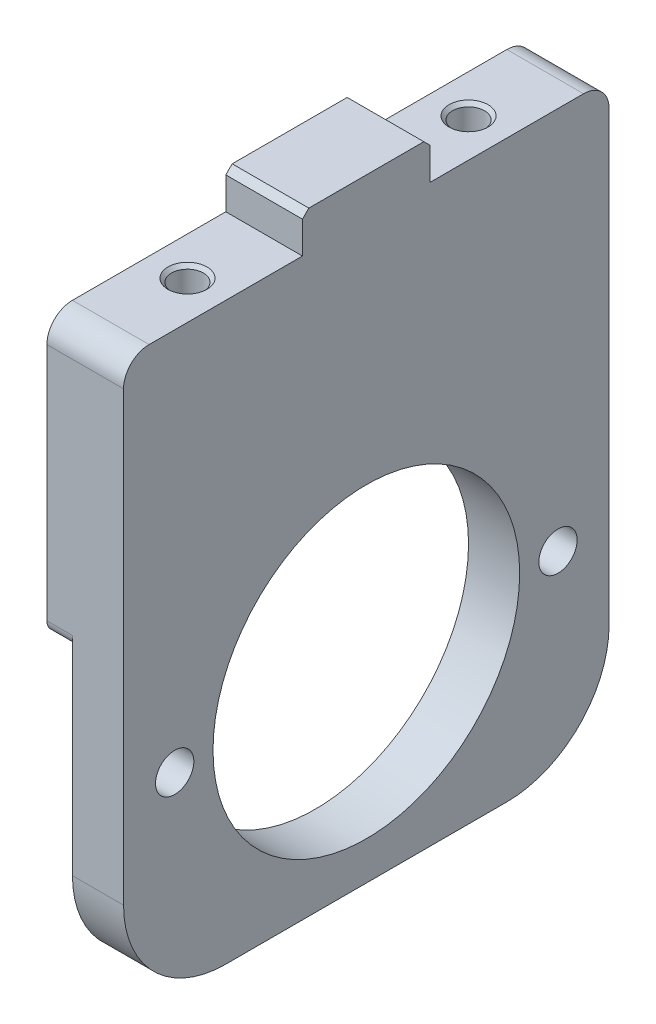
SolidWorks part; units mm, degrees
material "6061 合金"
ref_plane "前视基准面" through (0, 0, 0) normal (0, 0, 1) x (1, 0, 0)
ref_plane "上视基准面" through (0, 0, 0) normal (0, 1, 0) x (1, 0, 0)
ref_plane "右视基准面" through (0, 0, 0) normal (1, 0, 0) x (0, 0, -1)
sketch "草图1" plane through (0, 0, 0) normal (1, 0, 0) x (0, 0, -1)
  line L1 (-19, 22.5) -> (19, 22.5)
  line L2 (-19, 22.5) -> (-19, -22.5)
  line L3 (-19, -22.5) -> (19, -22.5)
  line L4 (19, 22.5) -> (19, -22.5)
  line L5 (-19, 22.5) -> (19, -22.5) construction
  line L6 (-19, -22.5) -> (19, 22.5) construction
  point P0 (0, 0)
  dimension "D1" = 45
  dimension "D2" = 38
extrude "凸台-拉伸1" add sketch "草图1" along normal blind 6
sketch "草图2" plane through (0, 0, 0) normal (-1, 0, 0) x (0, 0, 1)
  line L0 (0, 21.1574) -> (0, -25.7168) construction
  line L1 (0, -7.5) -> (15, -7.5) construction
  line L2 (19, -22.5) -> (-19, -22.5) construction
  circle A0 centre (0, -7.5) radius 12
  circle A1 centre (15, -7.5) radius 1.5
  circle A2 centre (-15, -7.5) radius 1.5
  dimension "D1" = 24
  dimension "D2" = 3
  dimension "D3" = 30
  dimension "D4" = 15
extrude "切除-拉伸1" cut sketch "草图2" against normal through all
sketch "草图3" plane through (0, 0, 0) normal (-1, 0, 0) x (0, 0, 1)
  line L0 (19.25, -7.5) -> (19.25, -22.5)
  line L1 (19, -22.5) -> (-19, -22.5) construction
  line L2 (-19.25, -7.5) -> (-19.25, -22.5)
  line L3 (-19.25, -22.5) -> (19.25, -22.5)
  arc A0 (19.25, -7.5) -> (-19.25, -7.5) centre (0, -7.5) ccw
  dimension "D1" = 38.5
extrude "切除-拉伸2" cut sketch "草图3" against normal blind 2
fillet "圆角2" radius 1 2 edges at (1, -4.4077, -19) (1, -4.4077, 19)
fillet "圆角3" radius 8 2 edges at (4, -22.5, -19) (4, -22.5, 19)
fillet "圆角4" radius 2 2 edges at (3, 22.5, -19) (3, 22.5, 19)
sketch "草图4" plane through (0, 0, 0) normal (-1, 0, 0) x (0, 0, 1)
  line L0 (-5, 22.5) -> (-5, 25.5)
  line L1 (-17, 22.5) -> (17, 22.5) construction
  line L2 (0, 31.3621) -> (0, 2.3349) construction
  line L3 (5, 22.5) -> (5, 25.5)
  line L4 (-5, 25.5) -> (5, 25.5)
  line L5 (-5, 22.5) -> (5, 22.5)
  dimension "D1" = 3
  dimension "D2" = 10
extrude "凸台-拉伸2" add sketch "草图4" against normal up to surface (6 mm away) up to face at (6, -7.5, -16.5)
chamfer "倒角1" distance 0.5 angle 45 2 edges at (3, 25.5, -5) (3, 25.5, 5)
sketch "草图5" plane through (0, 22.5, 0) normal (0, 1, 0) x (1, 0, 0)
  line L0 (3, 17) -> (3, -17) construction
  line L1 (6, 17) -> (0, 17) construction
  line L2 (0, -17) -> (6, -17) construction
  line L3 (-5.2576, 0) -> (13.9426, 0) construction
  point P6 (3, -11)
  point P9 (3, 11)
  dimension "D1" = 22
hole_wizard "M3 螺纹孔1" positions "3D草图2" profile "草图7" tap size "M3" standard "GB"
sketch3d "3D草图2"
  point P0 (3, 22.5, -11)
  point P2 (3, 22.5, 11)
  point P5 (3, 22.5, -11)
  point P7 (3, 22.5, 11)
sketch "草图7" plane through (3, 22.5, -11) normal (1, 0, 0) x (0, 0, 1)
  line L0 (0, 0) -> (0, 8.2511)
  line L1 (0, 8.2511) -> (1.25, 7.5)
  line L2 (1.25, 7.5) -> (1.25, 0.275)
  line L3 (1.25, 0.275) -> (1.525, 0)
  line L5 (1.525, 0) -> (0, 0)
  line L6 (-1.25, 0.275) -> (-1.525, 0) construction
  line L10 (0, 8.2511) -> (-1.25, 7.5) construction
  line L11 (0, -6.35) -> (0, 107.95) construction
  dimension "螺纹孔钻头直径" = 2.5
  dimension "螺纹孔钻头深度" = 7.5
  dimension "近端锥形沉头孔直径" = 3.05
  dimension "近端锥形沉头孔角度" = 90
  dimension "导头角度" = 118
cosmetic thread "孔螺蚊线1" parameters "D1"=6, "D2"=3
cosmetic thread "孔螺蚊线2" parameters "D1"=6, "D2"=3
